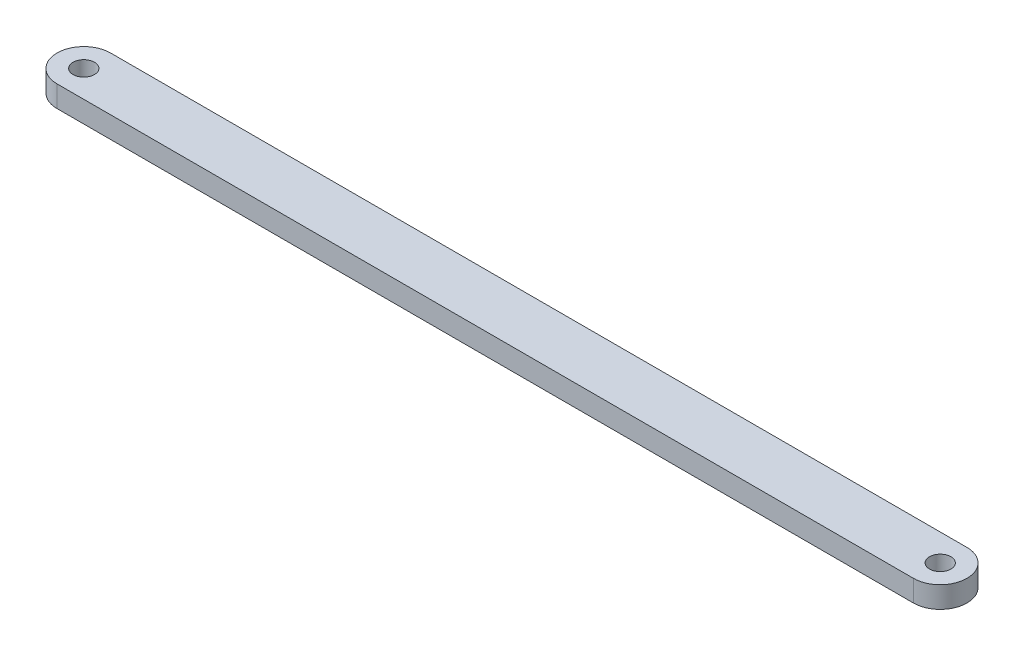
SolidWorks part; units mm, degrees
ref_plane "Front Plane" through (0, 0, 0) normal (0, 0, 1) x (1, 0, 0)
ref_plane "Top Plane" through (0, 0, 0) normal (0, 1, 0) x (1, 0, 0)
ref_plane "Right Plane" through (0, 0, 0) normal (1, 0, 0) x (0, 0, -1)
sketch "Sketch1" plane through (0, 0, 0) normal (0, 1, 0) x (1, 0, 0)
  line L0 (-10, 0) -> (70, 0) construction
  line L1 (-10, 2.5) -> (70, 2.5)
  line L2 (-10, -2.5) -> (70, -2.5)
  arc A0 (-10, 2.5) -> (-10, -2.5) centre (-10, 0) ccw
  arc A1 (70, -2.5) -> (70, 2.5) centre (70, 0) ccw
  circle A2 centre (70, 0) radius 1
  circle A3 centre (-10, 0) radius 1
  point P3 (30, 0)
  dimension "D3" = 2
  dimension "D4" = 2.5
  dimension "D5" = 2
  dimension "D1" = 80
  dimension "D12" = 10
extrude "Boss-Extrude1" add sketch "Sketch1" along normal blind 2
